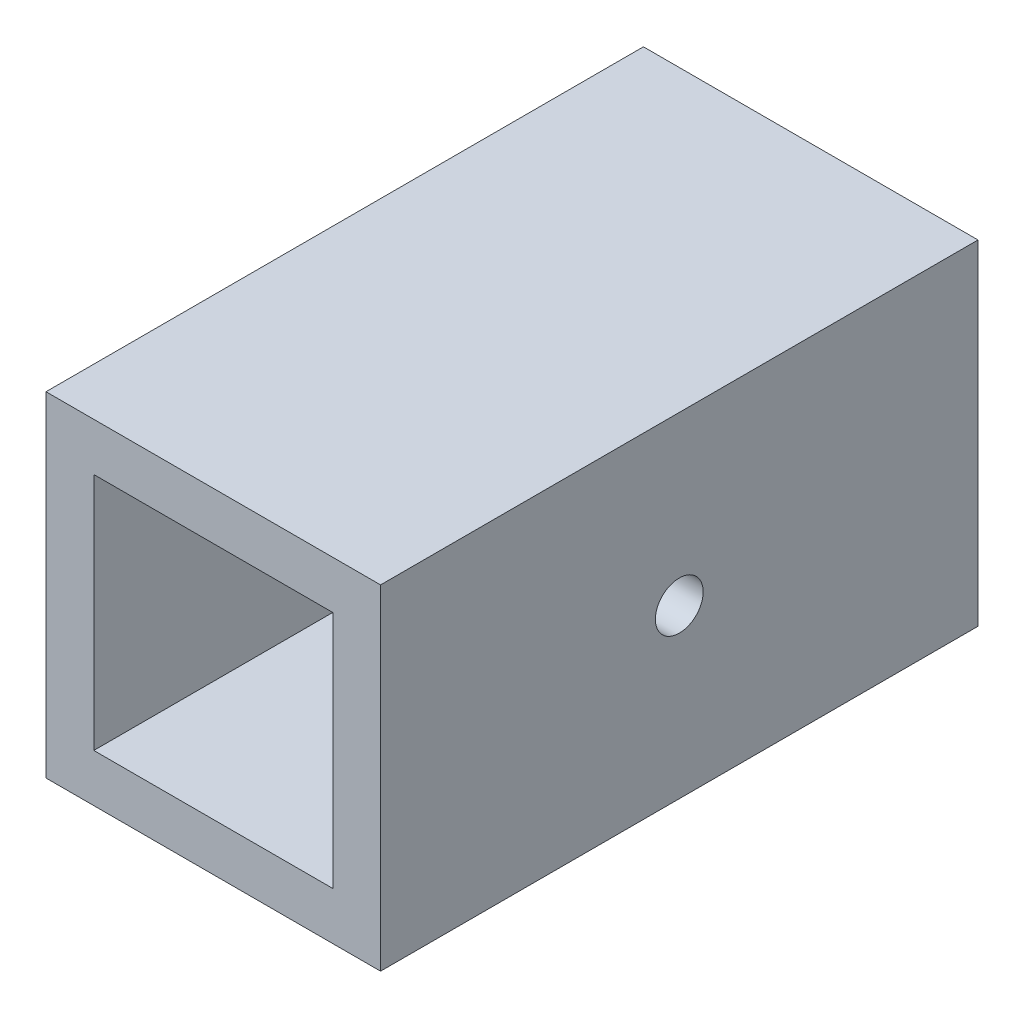
SolidWorks part; units mm, degrees
ref_plane "前视基准面" through (0, 0, 0) normal (0, 0, 1) x (1, 0, 0)
ref_plane "上视基准面" through (0, 0, 0) normal (0, 1, 0) x (1, 0, 0)
ref_plane "右视基准面" through (0, 0, 0) normal (1, 0, 0) x (0, 0, -1)
sketch "草图1" plane through (0, 0, 0) normal (0, 0, 1) x (1, 0, 0)
  line L1 (0, 0) -> (14, 0)
  line L2 (0, 0) -> (0, 14)
  line L3 (0, 14) -> (14, 14)
  line L4 (14, 0) -> (14, 14)
  line L5 (2, 2) -> (12, 2)
  line L6 (2, 2) -> (2, 12)
  line L7 (2, 12) -> (12, 12)
  line L8 (12, 2) -> (12, 12)
  point P5 (2, 2)
extrude "凸台-拉伸1" add sketch "草图1" along normal blind 10
sketch "草图2" plane through (0, 0, 10) normal (0, 0, 1) x (1, 0, 0)
  line L1 (0, 14) -> (14, 14)
  line L2 (0, 14) -> (0, 0)
  line L3 (0, 0) -> (14, 0)
  line L4 (14, 14) -> (14, 0)
extrude "凸台-拉伸2" add sketch "草图2" along normal blind 5
sketch "草图3" plane through (0, 0, 15) normal (0, 0, 1) x (1, 0, 0)
  line L1 (0, 14) -> (14, 14)
  line L2 (0, 14) -> (0, 0)
  line L3 (0, 0) -> (14, 0)
  line L4 (14, 14) -> (14, 0)
  line L5 (2, 12) -> (12, 12)
  line L6 (2, 12) -> (2, 2)
  line L7 (2, 2) -> (12, 2)
  line L8 (12, 12) -> (12, 2)
  point P6 (2, 12)
extrude "凸台-拉伸3" add sketch "草图3" along normal blind 10
sketch "草图4" plane through (14, 0, 0) normal (1, 0, 0) x (0, 0, -1)
  circle A0 centre (-11.5, 6) radius 1
  point P0 (-11.5, 6)
sketch "草图5" plane through (14, 0, 0) normal (1, 0, 0) x (0, 0, -1)
  circle A0 centre (-12.5, 6) radius 1
  point P0 (-12.5, 6)
sketch "草图6" plane through (14, 0, 0) normal (1, 0, 0) x (0, 0, -1)
  circle A0 centre (-12.5, 7) radius 1
  point P0 (-12.5, 7)
  point P3 (0, 0)
  point P6 (0, 0)
extrude "切除-拉伸1" cut sketch "草图6" against normal blind 16
